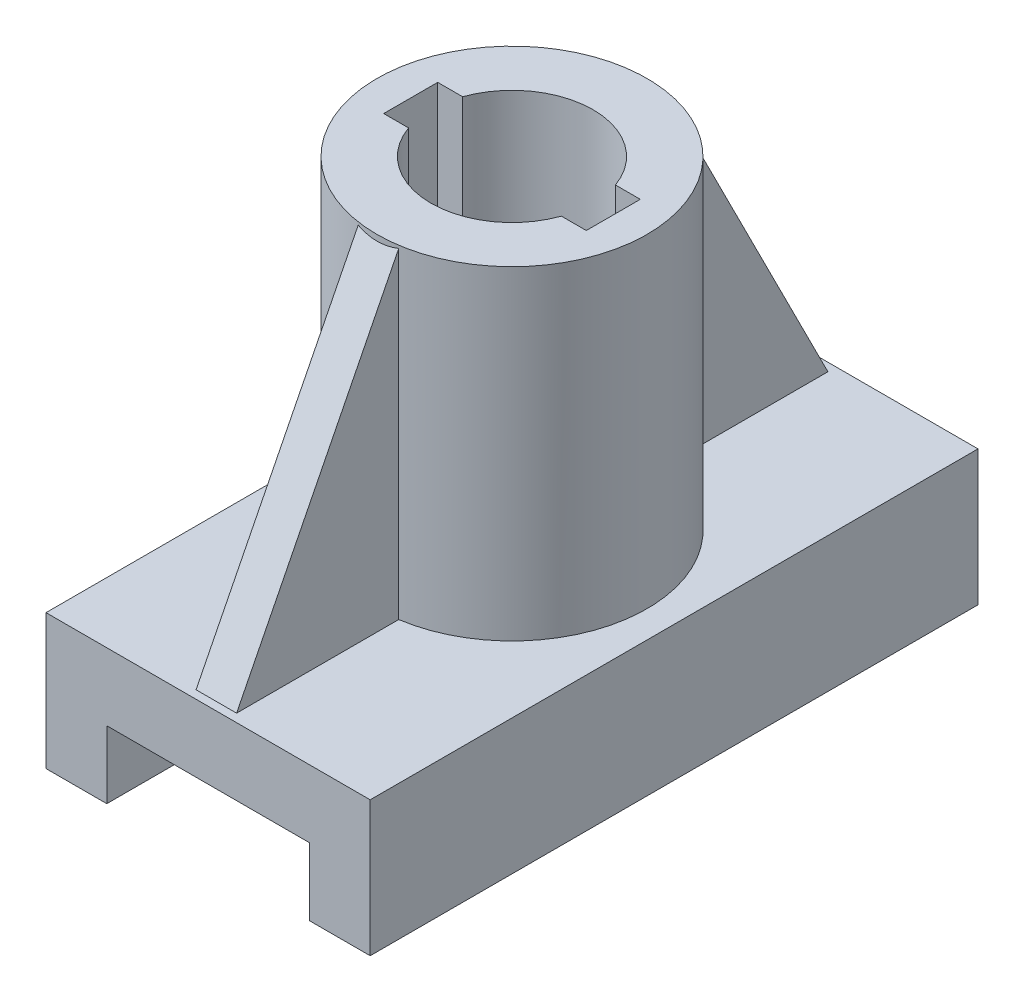
SolidWorks part; units mm, degrees
ref_plane "Спереди" through (0, 0, 0) normal (0, 0, 1) x (1, 0, 0)
ref_plane "Сверху" through (0, 0, 0) normal (0, 1, 0) x (1, 0, 0)
ref_plane "Справа" through (0, 0, 0) normal (1, 0, 0) x (0, 0, -1)
sketch "Эскиз1" plane through (0, 0, 0) normal (0, 0, 1) x (1, 0, 0)
  line L0 (-15, 0) -> (-15, 10)
  line L1 (-15, 0) -> (-24, 0)
  line L2 (-24, 0) -> (-24, 20)
  line L3 (-24, 20) -> (24, 20)
  line L4 (24, 20) -> (24, 0)
  line L5 (24, 0) -> (15, 0)
  line L6 (-15, 10) -> (15, 10)
  line L7 (15, 10) -> (15, 0)
  line L8 (0, 0) -> (-15, 0) construction
  line L9 (0, 0) -> (15, 0) construction
  point P10 (0, 0)
  point P11 (0, 0)
  dimension "D1" = 48
  dimension "D2" = 10
  dimension "D3" = 30
  dimension "D4" = 20
extrude "Бобышка-Вытянуть1" add sketch "Эскиз1" against normal blind 90
sketch "Эскиз2" plane through (0, 20, 0) normal (0, 1, 0) x (1, 0, 0)
  line L0 (0, 0) -> (0, 90) construction
  line L1 (24, 0) -> (-24, 0) construction
  line L2 (24, 90) -> (-24, 90) construction
  line L3 (20, 45) -> (-20, 45) construction
  line L5 (-11.3137, 49) -> (-15, 49)
  line L6 (15, 49) -> (11.3137, 49)
  line L7 (-11.3137, 41) -> (-15, 41)
  line L8 (-15, 49) -> (-15, 41)
  line L9 (15, 49) -> (15, 41)
  line L10 (15, 41) -> (11.3137, 41)
  circle A0 centre (0, 45) radius 20
  arc A1 (-11.3137, 41) -> (11.3137, 41) centre (0, 45) ccw
  arc A2 (11.3137, 49) -> (-11.3137, 49) centre (0, 45) ccw
  point P11 (-12, 45)
  point P13 (12, 45)
  point P14 (0, 0)
  point P19 (0, 0)
  point P20 (0, 0)
  dimension "D1" = 4
  dimension "D7" = 12
  dimension "D8" = 40
  dimension "D2" = 4
  dimension "D3" = 3
  dimension "D4" = 4
  dimension "D5" = 4
  dimension "D6" = 3
  dimension "D9" = 3.6863
extrude "Бобышка-Вытянуть2" add sketch "Эскиз2" along normal blind 48
sketch "Эскиз5" plane through (0, 0, 0) normal (1, 0, 0) x (0, 0, -1)
  line L0 (65, 67.1264) -> (88.7782, 20) construction
  line L1 (65, 20) -> (65, 68) construction
  line L2 (90, 20) -> (0, 20) construction
  line L3 (65, 20) -> (65, 68) construction
  line L4 (24.9979, 67.1264) -> (1.2197, 20)
  line L5 (44.9989, 19.2388) -> (44.9989, 88.8396) construction
  point P4 (0, 0)
  point P5 (0, 0)
  point P10 (0, 0)
  point P31 (89.9979, 20)
sketch "Эскиз7" plane through (0, 0, 0) normal (1, 0, 0) x (0, 0, -1)
  line L0 (65, 67.1264) -> (88.7782, 20)
  point P2 (65, 67.1264)
  point P4 (89.9979, 20)
  point P6 (89.9979, 20)
  point P7 (89.9979, 20)
  point P8 (88.7782, 20)
rib "Ребро44" sketch "Эскиз5" sketch "Эскиз5" thickness 6 extrusion direction parallel to sketch draft on no parameters "D1"=6
rib "Ребро45" sketch "Эскиз7" sketch "Эскиз7" thickness 6 extrusion direction parallel to sketch draft on no parameters "D1"=6
